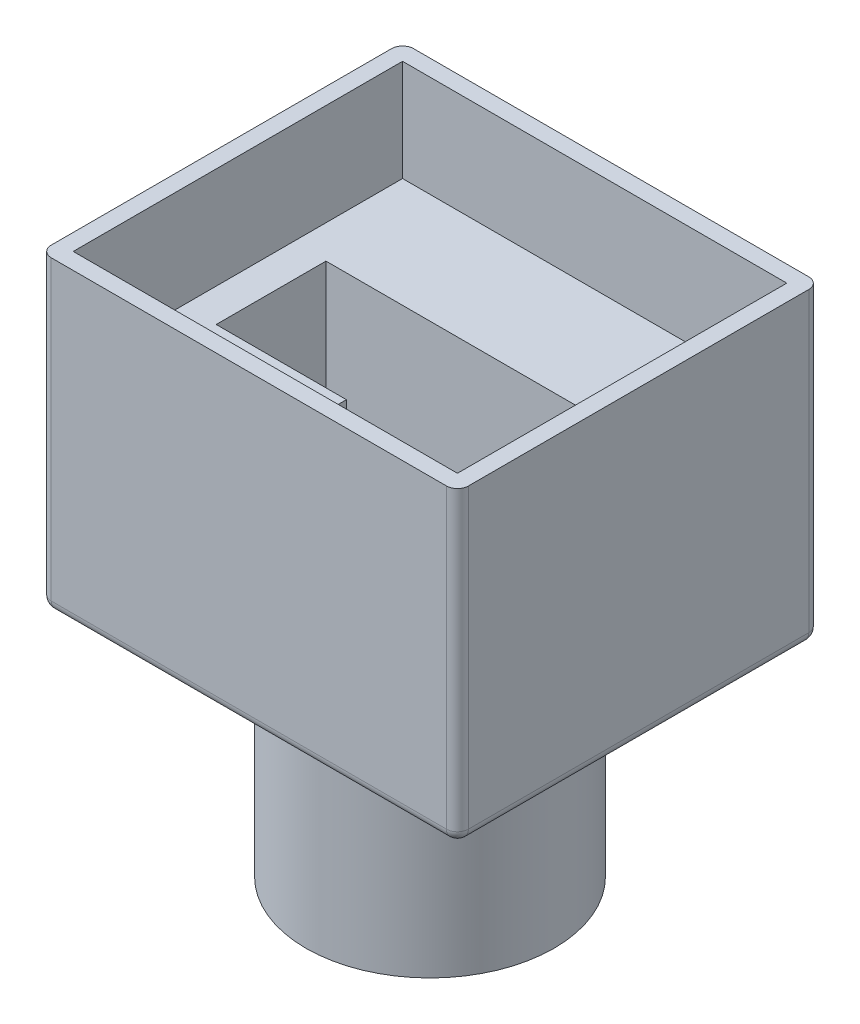
SolidWorks part; units mm, degrees
ref_plane "Front Plane" through (0, 0, 0) normal (0, 0, 1) x (1, 0, 0)
ref_plane "Top Plane" through (0, 0, 0) normal (0, 1, 0) x (1, 0, 0)
ref_plane "Right Plane" through (0, 0, 0) normal (1, 0, 0) x (0, 0, -1)
sketch "Sketch1" plane through (0, 0, 0) normal (0, 1, 0) x (1, 0, 0)
  line L1 (-35, -30) -> (35, -30)
  line L2 (-35, -30) -> (-35, 30)
  line L3 (-35, 30) -> (35, 30)
  line L4 (35, -30) -> (35, 30)
  line L5 (-35, -30) -> (35, 30) construction
  line L6 (-35, 30) -> (35, -30) construction
  line L7 (-38, -33) -> (38, -33)
  line L8 (-38, -33) -> (-38, 33)
  line L9 (-38, 33) -> (38, 33)
  line L10 (38, -33) -> (38, 33)
  line L11 (-38, -33) -> (38, 33) construction
  line L12 (-38, 33) -> (38, -33) construction
  point P0 (0, 0)
  point P6 (0, 0)
  dimension "D1" = 60
  dimension "D2" = 70
  dimension "D3" = 3
  dimension "D4" = 3
extrude "Boss-Extrude1" add sketch "Sketch1" along normal blind 18.5
sketch "Sketch2" plane through (0, 0, 0) normal (0, -1, 0) x (1, 0, 0)
  line L0 (-5.225, 10) -> (-5.225, 30)
  line L1 (-28.95, 10) -> (18.5, 10)
  line L2 (-28.95, 10) -> (-28.95, -10)
  line L3 (-28.95, -10) -> (18.5, -10)
  line L4 (18.5, 10) -> (18.5, -10)
  line L5 (-28.95, 10) -> (18.5, -10) construction
  line L6 (-28.95, -10) -> (18.5, 10) construction
  line L7 (-35, 30) -> (35, 30) construction
  line L8 (18.5, -5) -> (35, -5)
  line L9 (35, 30) -> (35, -30) construction
  point P0 (-5.225, 0)
  line M6 (38, -33) -> (38, 33)
  line M7 (38, 33) -> (-38, 33)
  line M8 (-38, 33) -> (-38, -33)
  line M9 (-38, -33) -> (38, -33)
  line M10 (-35, 30) -> (35, 30)
  line M11 (35, 30) -> (35, -30)
  line M12 (35, -30) -> (-35, -30)
  line M13 (-35, -30) -> (-35, 30)
  dimension "D1" = 28.95
  dimension "D2" = 47.45
  dimension "D3" = 20
  dimension "D4" = 5
extrude "Boss-Extrude2" add sketch "Sketch2" along normal blind 27.65 contours L8 L4 L3 L2 L1 L0 M10 M13 M12 M11 | M9 M6 M7 M8 M13 M10 M11 M12
sketch "Sketch4" plane through (0, -27.65, 0) normal (0, -1, 0) x (1, 0, 0)
  line L1 (-38, 33) -> (38, 33)
  line L2 (-38, 33) -> (-38, -33)
  line L3 (-38, -33) -> (38, -33)
  line L4 (38, 33) -> (38, -33)
  line L5 (-38, 33) -> (38, -33) construction
  line L6 (-38, -33) -> (38, 33) construction
  point P0 (0, 0)
extrude "Boss-Extrude3" add sketch "Sketch4" along normal blind 10
sketch "Sketch5" plane through (0, -37.65, 0) normal (0, -1, 0) x (1, 0, 0)
  circle A0 centre (0, 0) radius 22.6
  circle A1 centre (0, 0) radius 19.6
  dimension "D1" = 45.2
  dimension "D2" = 3
extrude "Boss-Extrude4" add sketch "Sketch5" along normal blind 40
fillet "Fillet1" radius 2 4 edges at (38, -9.575, -33) (-38, -9.575, -33) (38, -9.575, 33) (-38, -9.575, 33)
fillet "Fillet2" radius 2 8 edges at (-37.4142, -37.65, 32.4142) (37.4142, -37.65, 32.4142) (37.4142, -37.65, -32.4142) (-37.4142, -37.65, -32.4142) (0, -37.65, 33) (38, -37.65, 0) (0, -37.65, -33) (-38, -37.65, 0)
